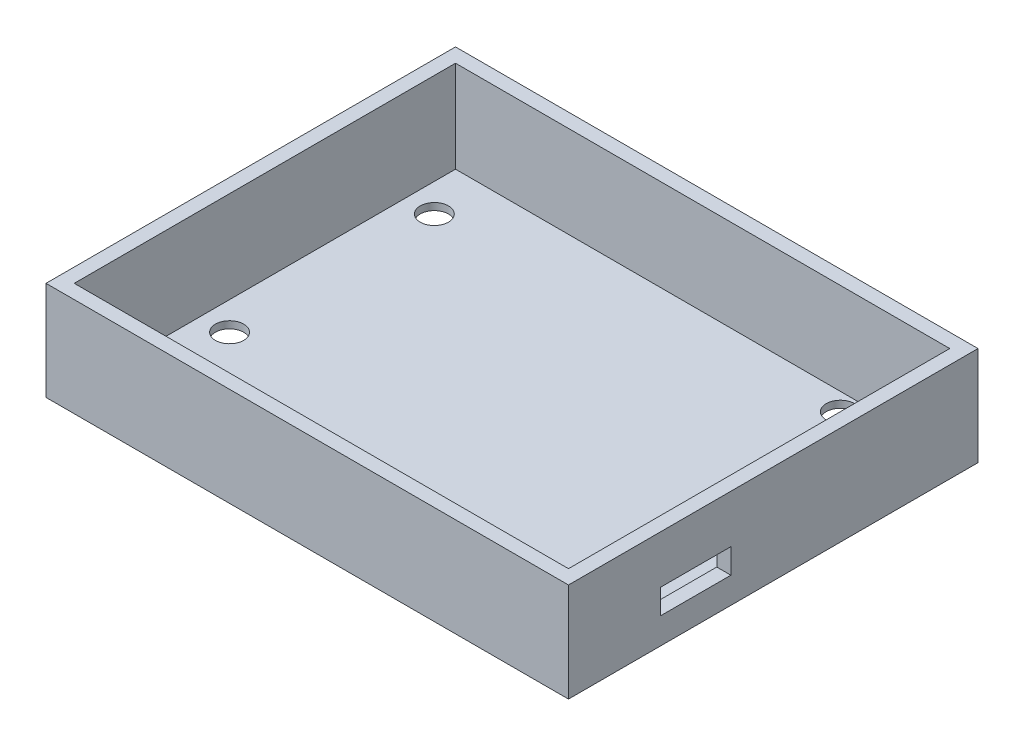
SolidWorks part; units mm, degrees
ref_plane "Ön Düzlem" through (0, 0, 0) normal (0, 0, 1) x (1, 0, 0)
ref_plane "Üst Düzlem" through (0, 0, 0) normal (0, 1, 0) x (1, 0, 0)
ref_plane "Sağ Düzlem" through (0, 0, 0) normal (1, 0, 0) x (0, 0, -1)
sketch "Çizim1" plane through (0, 0, 0) normal (0, 1, 0) x (1, 0, 0)
  line L1 (36, -28) -> (-36, -28)
  line L2 (36, -28) -> (36, 28)
  line L3 (36, 28) -> (-36, 28)
  line L4 (-36, -28) -> (-36, 28)
  line L5 (36, -28) -> (-36, 28) construction
  line L6 (36, 28) -> (-36, -28) construction
  point P0 (0, 0)
  dimension "D1" = 72
  dimension "D2" = 56
extrude "Yükseklik-Ekstrüzyon2" add sketch "Çizim1" along normal blind 1
sketch "Çizim3" plane through (0, 1, 0) normal (0, 1, 0) x (1, 0, 0)
  line L1 (-36, 28) -> (36, 28)
  line L2 (-36, 28) -> (-36, -28)
  line L3 (-36, -28) -> (36, -28)
  line L4 (36, 28) -> (36, -28)
extrude "Ekstrüzyon-İnce2" add sketch "Çizim3" along normal blind 13 thin
sketch "Çizim4" plane through (35, 0, 0) normal (-1, 0, 0) x (0, 0, 1)
  line L0 (27, 14) -> (27, 1) construction
  line L1 (25.9, 6) -> (15.9, 6)
  line L2 (25.9, 6) -> (25.9, 2)
  line L3 (25.9, 2) -> (15.9, 2)
  line L4 (15.9, 6) -> (15.9, 2)
  line L5 (27, 1) -> (-27, 1) construction
  dimension "D1" = 1.1
  dimension "D2" = 10
  dimension "D3" = 1
  dimension "D4" = 4
extrude "Kes-Ekstrüzyon1" cut sketch "Çizim4" against normal blind 1
sketch "Çizim5" plane through (0, 1, 0) normal (0, 1, 0) x (1, 0, 0)
  line L0 (35, -27) -> (35, 27) construction
  line L1 (-35, -27) -> (35, -27) construction
  line L2 (35, -27) -> (35, 27) construction
  line L3 (35, 27) -> (-35, 27) construction
  line L5 (35, 27) -> (-35, 27) construction
  circle A0 centre (19.5, -24) radius 2
  circle A1 centre (22, 24.5) radius 2
  circle A2 centre (-31, -9) radius 2
  circle A3 centre (-31, 20) radius 2
  dimension "D2" = 3
  dimension "D5" = 66
  dimension "D7" = 66
  dimension "D1" = 15.5
  dimension "D3" = 13
  dimension "D4" = 2.5
  dimension "D6" = 18
  dimension "D8" = 7
extrude "Kes-Ekstrüzyon2" cut sketch "Çizim5" against normal blind 1
sketch "Çizim6" plane through (0, 0, 28) normal (0, 0, 1) x (1, 0, 0)
  line L0 (-36, 0) -> (36, 0) construction
  line L1 (36, 14) -> (35, 14)
  line L2 (36, 14) -> (36, 0)
  line L3 (36, 0) -> (35, 0)
  line L4 (35, 14) -> (35, 0)
  dimension "D1" = 1
extrude "Yükseklik-Ekstrüzyon3" add sketch "Çizim6" against normal up to surface (56 mm away) up to face at (0, 7, -28)
sketch "Çizim7" plane through (35, 0, 0) normal (-1, 0, 0) x (0, 0, 1)
  line L0 (27, 14) -> (27, 1) construction
  line L1 (6, 5.2) -> (16, 5.2)
  line L2 (6, 5.2) -> (6, 2.2)
  line L3 (6, 2.2) -> (16, 2.2)
  line L4 (16, 5.2) -> (16, 2.2)
  line L5 (27, 1) -> (-27, 1) construction
  dimension "D1" = 10
  dimension "D2" = 11
  dimension "D3" = 3
  dimension "D4" = 1.2
extrude "Kes-Ekstrüzyon3" cut sketch "Çizim7" against normal blind 1
sketch "Çizim8" plane through (0, 1, 0) normal (0, 1, 0) x (1, 0, 0)
  line L0 (-36, 28) -> (-36, -28) construction
  line L1 (-37, 29) -> (37, 29)
  line L2 (-37, 29) -> (-37, -29)
  line L3 (-37, -29) -> (37, -29)
  line L4 (37, 29) -> (37, -29)
  line L5 (36, 28) -> (-36, 28) construction
  line L6 (36, -28) -> (36, 28) construction
  line L7 (-36, -28) -> (36, -28) construction
  dimension "D1" = 1
  dimension "D2" = 1
  dimension "D3" = 1
  dimension "D4" = 1
extrude "Ekstrüzyon-İnce4" add sketch "Çizim8" along normal up to surface (13 mm away) thin
sketch "Çizim9" plane through (35, 0, 0) normal (-1, 0, 0) x (0, 0, 1)
  line L0 (16, 5.2) -> (6, 5.2) construction
  line L1 (6, 7.2) -> (16, 7.2)
  line L2 (6, 7.2) -> (6, 2.2)
  line L3 (6, 2.2) -> (16, 2.2)
  line L4 (16, 7.2) -> (16, 2.2)
  dimension "D1" = 2
extrude "Kes-Ekstrüzyon4" cut sketch "Çizim9" against normal up to vertex (1 mm away)
sketch "Çizim10" plane through (35, 0, 0) normal (-1, 0, 0) x (0, 0, 1)
  line L0 (16, 2.2) -> (16, 7.2) construction
  line L1 (6, 2.2) -> (16, 2.2)
  line L2 (6, 2.2) -> (6, 3.7)
  line L3 (6, 3.7) -> (16, 3.7)
  line L4 (16, 2.2) -> (16, 3.7)
  dimension "D1" = 1.5
extrude "Yükseklik-Ekstrüzyon4" add sketch "Çizim10" against normal up to surface (2 mm away) up to face at (37, 7.5, 0)
sketch "Çizim11" plane through (35, 0, 0) normal (-1, 0, 0) x (0, 0, 1)
  line L1 (6, 7.2) -> (16, 7.2)
  line L2 (6, 7.2) -> (6, 3.7)
  line L3 (6, 3.7) -> (16, 3.7)
  line L4 (16, 7.2) -> (16, 3.7)
extrude "Kes-Ekstrüzyon5" cut sketch "Çizim11" against normal blind 2
sketch "Çizim12" plane through (0, 1, 0) normal (0, -1, 0) x (1, 0, 0)
  line L1 (-37, 29) -> (37, 29)
  line L2 (-37, 29) -> (-37, -29)
  line L3 (-37, -29) -> (37, -29)
  line L4 (37, 29) -> (37, -29)
extrude "Ekstrüzyon-İnce5" add sketch "Çizim12" along normal up to surface (1 mm away) thin
